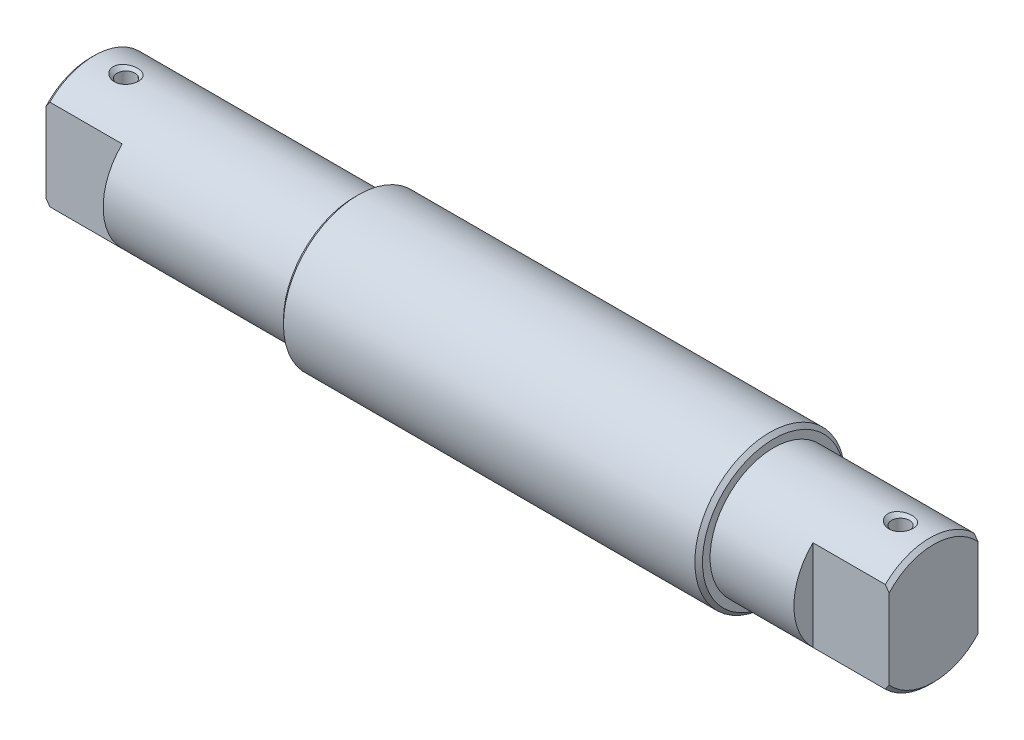
SolidWorks part; units mm, degrees
material "Ti-6Al-4V Обработанный раствором и остаренный (SS)"
ref_plane "Спереди" through (0, 0, 0) normal (0, 0, 1) x (1, 0, 0)
ref_plane "Сверху" through (0, 0, 0) normal (0, 1, 0) x (1, 0, 0)
ref_plane "Справа" through (0, 0, 0) normal (1, 0, 0) x (0, 0, -1)
sketch "Эскиз1" plane through (0, 0, 0) normal (0, 0, 1) x (1, 0, 0)
  line L0 (0, 0) -> (-50000, 0) construction
  line L1 (-186.5, 0) -> (-186.5, 25)
  line L6 (82.5, 25) -> (145.5, 25)
  line L7 (145.5, 25) -> (145.5, 0)
  line L8 (145.5, 0) -> (-186.5, 0)
  line L12 (-82.5, 25) -> (-82.5, 29.5)
  line L13 (-82.5, 29.5) -> (82.5, 29.5)
  line L14 (82.5, 29.5) -> (82.5, 25)
  line L15 (-186.5, 25) -> (-82.5, 25)
  line L16 (0, 0) -> (0, 50000) construction
  dimension "D1" = 165
  dimension "D3" = 104
  dimension "D4" = 332
  dimension "D5" = 50
  dimension "D7" = 59
revolve "Повернуть1" add sketch "Эскиз1" angle 360 about L0
sketch "Эскиз2" plane through (0, 0, 0) normal (0, 1, 0) x (1, 0, 0)
  line L0 (-186.5, 17.5) -> (-156.5, 17.5)
  line L1 (-186.5, 25) -> (-186.5, -25) construction
  line L2 (-156.5, 17.5) -> (-156.5, 25)
  line L3 (-82.5, 25) -> (-186.5, 25) construction
  line L4 (-156.5, 25) -> (-186.5, 25)
  line L5 (-186.5, 25) -> (-186.5, 17.5)
  line L6 (0, 0) -> (-50000, 0) construction
  line L7 (-186.5, -25) -> (-186.5, -17.5)
  line L8 (-156.5, -25) -> (-186.5, -25)
  line L9 (-156.5, -17.5) -> (-156.5, -25)
  line L10 (-186.5, -17.5) -> (-156.5, -17.5)
  line L11 (0, 0) -> (0, 50000) construction
  line L12 (145.5, 17.5) -> (115.5, 17.5)
  line L13 (145.5, -25) -> (145.5, 25) construction
  line L14 (115.5, 17.5) -> (115.5, 25)
  line L15 (145.5, 25) -> (82.5, 25) construction
  line L16 (115.5, 25) -> (145.5, 25)
  line L17 (145.5, 25) -> (145.5, 17.5)
  line L18 (145.5, -25) -> (145.5, -17.5)
  line L19 (115.5, -25) -> (145.5, -25)
  line L20 (115.5, -17.5) -> (115.5, -25)
  line L21 (145.5, -17.5) -> (115.5, -17.5)
  dimension "D1" = 30
  dimension "D2" = 35
  dimension "D3" = 30
extrude "Вырез-Вытянуть1" cut sketch "Эскиз2" against normal through all both and the other way through all
chamfer "Фаска1" distance 1.5 angle 45 6 edges at (145.5, 25, 0) (145.5, -25, 0) (-186.5, -25, 0) (-186.5, 25, 0) (82.5, 0, -29.5) (-82.5, 0, -29.5)
hole_wizard "Отверстие обработанное метчиком M8x1.01" positions "Трехмерный эскиз6" profile "Эскиз9" tap size "M8x1.0" standard "DIN"
sketch3d "Трехмерный эскиз6"
  point P0 (-172.5, 25, 0)
  point P7 (132.5, 25, 0)
sketch "Эскиз9" plane through (-172.5, 25, 0) normal (1, 0, 0) x (0, 0, 1)
  line L0 (0, 0) -> (0, 22.103)
  line L1 (0, 22.103) -> (3.5, 20)
  line L2 (3.5, 20) -> (3.5, 1.5)
  line L3 (3.5, 1.5) -> (5, 0)
  line L5 (5, 0) -> (0, 0)
  line L6 (-3.5, 1.5) -> (-5, 0) construction
  line L10 (0, 22.103) -> (-3.5, 20) construction
  line L11 (0, -6.35) -> (0, 107.95) construction
  dimension "Диаметр сверла" = 7
  dimension "Глубина сверла" = 20
  dimension "Диаметр передней зенковки" = 10
  dimension "Угол передней зенковки" = 90
  dimension "Угол заточки сверла" = 118
cosmetic thread "Отверстие резьбы1" parameters "D1"=16, "D2"=8
cosmetic thread "Отверстие резьбы2" parameters "D1"=16, "D2"=8
